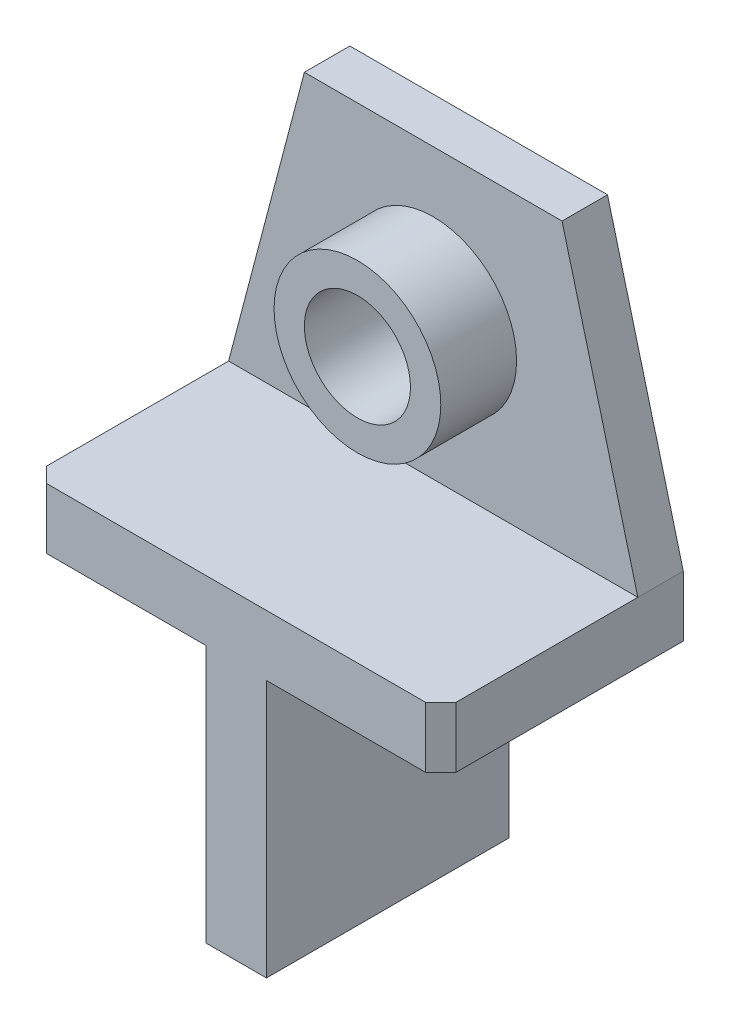
SolidWorks part; units mm, degrees
ref_plane "Front Plane" through (0, 0, 0) normal (0, 0, 1) x (1, 0, 0)
ref_plane "Top Plane" through (0, 0, 0) normal (0, 1, 0) x (1, 0, 0)
ref_plane "Right Plane" through (0, 0, 0) normal (1, 0, 0) x (0, 0, -1)
sketch "Sketch1" plane through (0, 0, 0) normal (0, 0, 1) x (1, 0, 0)
  line L0 (0, -1.7083) -> (0, 32.2917)
  line L1 (0, 32.2917) -> (-23, 32.2917)
  line L2 (-23, 32.2917) -> (-23, 40.2917)
  line L3 (-23, 40.2917) -> (31, 40.2917)
  line L4 (31, 40.2917) -> (31, 32.2917)
  line L5 (31, 32.2917) -> (8, 32.2917)
  line L8 (8, -1.7083) -> (0, -1.7083)
  line L9 (8, 32.2917) -> (8, -1.7083)
  dimension "D1" = 8
  dimension "D2" = 34
  dimension "D3" = 54
  dimension "D4" = 23
  dimension "D5" = 23
  dimension "D6" = 8
extrude "Boss-Extrude1" add sketch "Sketch1" against normal blind 32
chamfer "Chamfer1" distance 2 angle 45 2 edges at (-23, 36.2917, 0) (31, 36.2917, 0)
sketch "Sketch5" plane through (0, 0, -32) normal (0, 0, -1) x (-1, 0, 0)
  line L0 (23, 40.2917) -> (-31, 40.2917)
  line L2 (13, 78.2917) -> (-21, 78.2917)
  line L3 (13, 78.2917) -> (23, 40.2917)
  line L4 (-21, 78.2917) -> (-31, 40.2917)
  point P7 (-4, 78.2917)
  dimension "D1" = 38
  dimension "D2" = 34
  dimension "D3" = 39.2938
extrude "Boss-Extrude2" add sketch "Sketch5" against normal blind 6
sketch "Sketch11" plane through (0, 0, -26) normal (0, 0, 1) x (1, 0, 0)
  line L0 (4, 40.2917) -> (4, 59.2917) construction
  line L1 (31, 40.2917) -> (-23, 40.2917) construction
  circle A0 centre (4, 59.2917) radius 11
  circle A1 centre (4, 59.2917) radius 7
  dimension "D1" = 22
  dimension "D2" = 14
  dimension "D3" = 19
extrude "Boss-Extrude3" add sketch "Sketch11" along normal blind 10
sketch "Sketch14" plane through (0, 0, -26) normal (0, 0, 1) x (1, 0, 0)
  circle A0 centre (4, 59.2917) radius 7
  dimension "D1" = 14
extrude "Cut-Extrude1" cut sketch "Sketch14" against normal blind 6
